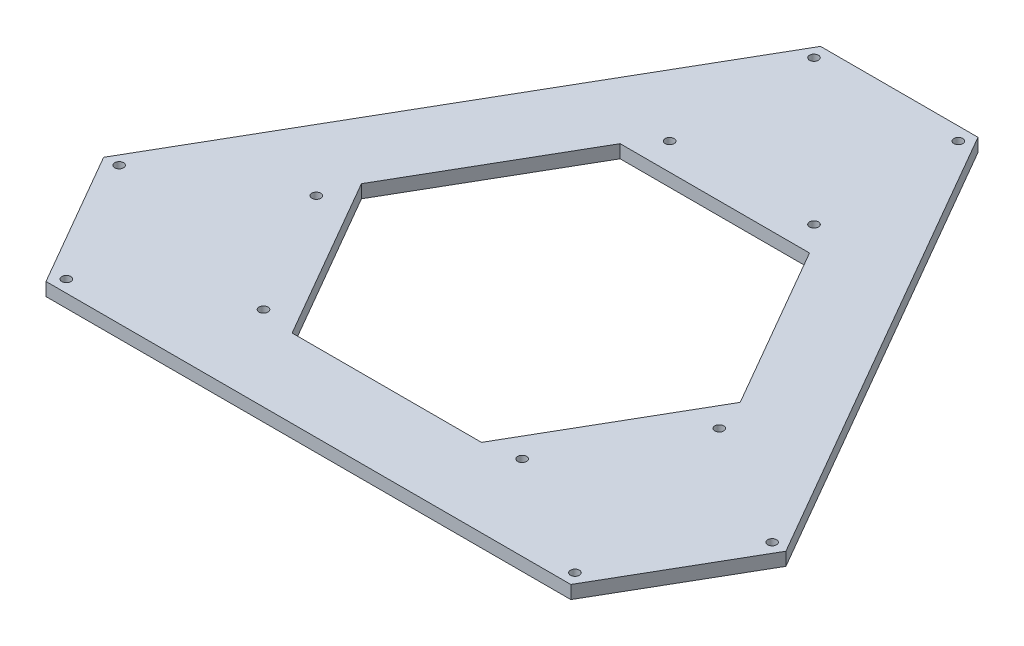
SolidWorks part; units mm, degrees
material "PVC Rigid"
ref_plane "Front Plane" through (0, 0, 0) normal (0, 0, 1) x (1, 0, 0)
ref_plane "Top Plane" through (0, 0, 0) normal (0, 1, 0) x (1, 0, 0)
ref_plane "Right Plane" through (0, 0, 0) normal (1, 0, 0) x (0, 0, -1)
sketch "Sketch1" plane through (0, 0, 0) normal (0, 1, 0) x (1, 0, 0)
  line L0 (-30, 132.7906) -> (30, 132.7906)
  line L1 (30, 132.7906) -> (130, -40.4145)
  line L2 (130, -40.4145) -> (100, -92.376)
  line L3 (100, -92.376) -> (-100, -92.376)
  line L4 (-100, -92.376) -> (-130, -40.4145)
  line L5 (-130, -40.4145) -> (-30, 132.7906)
  line L6 (-80, 46.188) -> (115, -66.3953) construction
  line L7 (-115, -66.3953) -> (80, 46.188) construction
  line L8 (0, 132.7906) -> (0, -92.376) construction
  line L10 (-72.1688, 0) -> (-36.0844, -62.5)
  line L11 (-36.0844, -62.5) -> (36.0844, -62.5)
  line L12 (36.0844, -62.5) -> (72.1688, 0)
  line L13 (72.1688, 0) -> (36.0844, 62.5)
  line L14 (36.0844, 62.5) -> (-36.0844, 62.5)
  line L15 (-36.0844, 62.5) -> (-72.1688, 0)
  circle A0 centre (-27.5, 127.7906) radius 1.7
  circle A1 centre (-27.5, 72.7906) radius 1.7
  circle A2 centre (27.5, 127.7906) radius 1.7
  circle A3 centre (27.5, 72.7906) radius 1.7
  circle A4 centre (76.7885, -12.5796) radius 1.7
  circle A5 centre (49.2885, -60.211) radius 1.7
  circle A6 centre (96.9199, -87.711) radius 1.7
  circle A7 centre (124.4199, -40.0796) radius 1.7
  circle A8 centre (-49.2885, -60.211) radius 1.7
  circle A9 centre (-76.7885, -12.5796) radius 1.7
  circle A10 centre (-124.4199, -40.0796) radius 1.7
  circle A11 centre (-96.9199, -87.711) radius 1.7
  circle A12 centre (0, 0) radius 62.5 construction
  point P13 (0, 0)
  point P42 (0, 0)
  dimension "D2" = 200
  dimension "D5" = 3.4
  dimension "D8" = 125
  dimension "D1" = 60
  dimension "D3" = 55
  dimension "D4" = 55
  dimension "D6" = 5
  dimension "D7" = 3
extrude "Boss-Extrude1" add sketch "Sketch1" along normal blind 5
